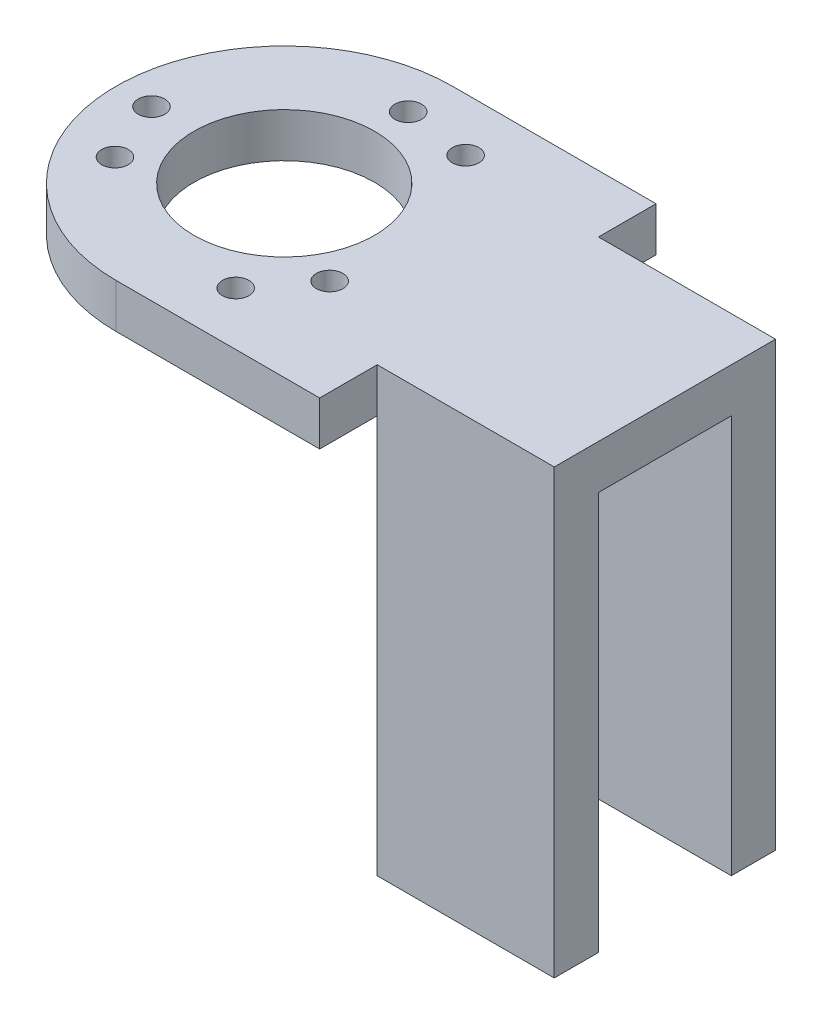
SolidWorks part; units mm, degrees
ref_plane "Front Plane" through (0, 0, 0) normal (0, 0, 1) x (1, 0, 0)
ref_plane "Top Plane" through (0, 0, 0) normal (0, 1, 0) x (1, 0, 0)
ref_plane "Right Plane" through (0, 0, 0) normal (1, 0, 0) x (0, 0, -1)
sketch "Sketch1" plane through (0, 0, 0) normal (0, 1, 0) x (1, 0, 0)
  circle A0 centre (0, 0) radius 19
  circle A1 centre (0, 0) radius 10.2
extrude "Boss-Extrude1" add sketch "Sketch1" along normal blind 5
sketch "Sketch2" plane through (0, 5, 0) normal (0, 1, 0) x (1, 0, 0)
  line L0 (0, 0) -> (0, 14)
  line L1 (0, 0) -> (7.5, 12.9904)
  line L2 (0, 0) -> (12.1244, -7)
  line L3 (0, 0) -> (7.5, -12.9904)
  line L4 (0, 0) -> (-12.1244, -7)
  line L5 (0, 0) -> (-15, 0)
  circle A0 centre (0, 0) radius 14
  circle A1 centre (0, 0) radius 15
  circle A2 centre (0, 14) radius 1.5
  circle A3 centre (7.5, 12.9904) radius 1.5
  circle A4 centre (12.1244, -7) radius 1.5
  circle A5 centre (7.5, -12.9904) radius 1.5
  circle A6 centre (-12.1244, -7) radius 1.5
  circle A7 centre (-15, 0) radius 1.5
  dimension "D1" = 30
extrude "Cut-Extrude1" cut sketch "Sketch2" against normal blind 5 contours A1 A3 | A0 A3 A1 L1 | L1 A3 A0 | A0 A3 L1 | A1 A3 A0 L1 | L5 A7 A0 | A0 A7 L5 | A0 A7 A1 L5 | A1 A7 A0 L5 | A1 A7 | A1 A6 | A0 A6 A1 | L4 A6 A0 | A0 A6 L4 | L3 A5 A0 | A0 A5 L3 | A0 A5 A1 L3 | A1 A5 A0 L3 | A1 A5 | L2 A4 A0 | A0 A4 L2 | A1 A4 A0 | A1 A4 | A2
sketch "Sketch3" plane through (0, 5, 0) normal (0, 1, 0) x (1, 0, 0)
  line L2 (0, 0) -> (0, 19)
  line L3 (0, 19) -> (23, 19)
  line L6 (0, 0) -> (0, -19)
  line L7 (0, -19) -> (23, -19)
  line L10 (23, 19) -> (23, -19)
extrude "Boss-Extrude2" add sketch "Sketch3" against normal blind 5
sketch "Sketch7" plane through (23, 0, 0) normal (1, 0, 0) x (0, 0, -1)
  line L7 (-12.5, 5) -> (12.5, 5)
  line L8 (-12.5, 5) -> (-12.5, 0)
  line L9 (-12.5, 0) -> (12.5, 0)
  line L10 (12.5, 5) -> (12.5, 0)
  point P0 (0, 0)
extrude "Boss-Extrude5" add sketch "Sketch7" along normal blind 20
sketch "Sketch8" plane through (0, 0, 12.5) normal (0, 0, 1) x (1, 0, 0)
  line L1 (23, 5) -> (43, 5)
  line L2 (23, 5) -> (23, -45)
  line L3 (23, -45) -> (43, -45)
  line L4 (43, 5) -> (43, -45)
extrude "Boss-Extrude6" add sketch "Sketch8" against normal blind 5
sketch "Sketch9" plane through (0, 0, -12.5) normal (0, 0, -1) x (-1, 0, 0)
  line L1 (-43, 5) -> (-23, 5)
  line L2 (-43, 5) -> (-43, -45)
  line L3 (-43, -45) -> (-23, -45)
  line L4 (-23, 5) -> (-23, -45)
extrude "Boss-Extrude7" add sketch "Sketch9" against normal blind 5
